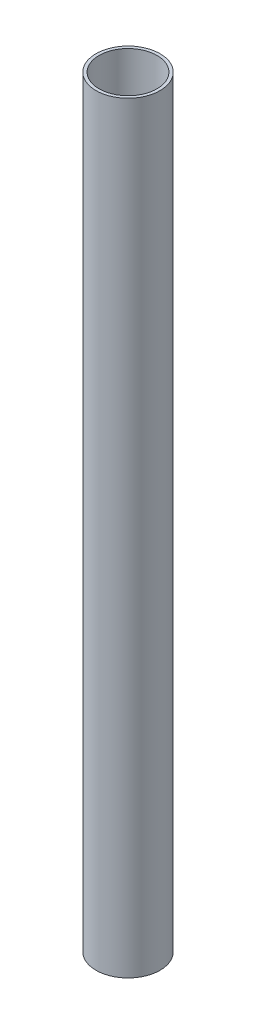
SolidWorks part; units mm, degrees
ref_plane "Front Plane" through (0, 0, 0) normal (0, 0, 1) x (1, 0, 0)
ref_plane "Top Plane" through (0, 0, 0) normal (0, 1, 0) x (1, 0, 0)
ref_plane "Right Plane" through (0, 0, 0) normal (1, 0, 0) x (0, 0, -1)
sketch "Sketch1" plane through (0, 0, 0) normal (0, 1, 0) x (1, 0, 0)
  circle A0 centre (0, 0) radius 9.5
extrude "Extrude-Thin1" add sketch "Sketch1" along normal blind 250 thin
